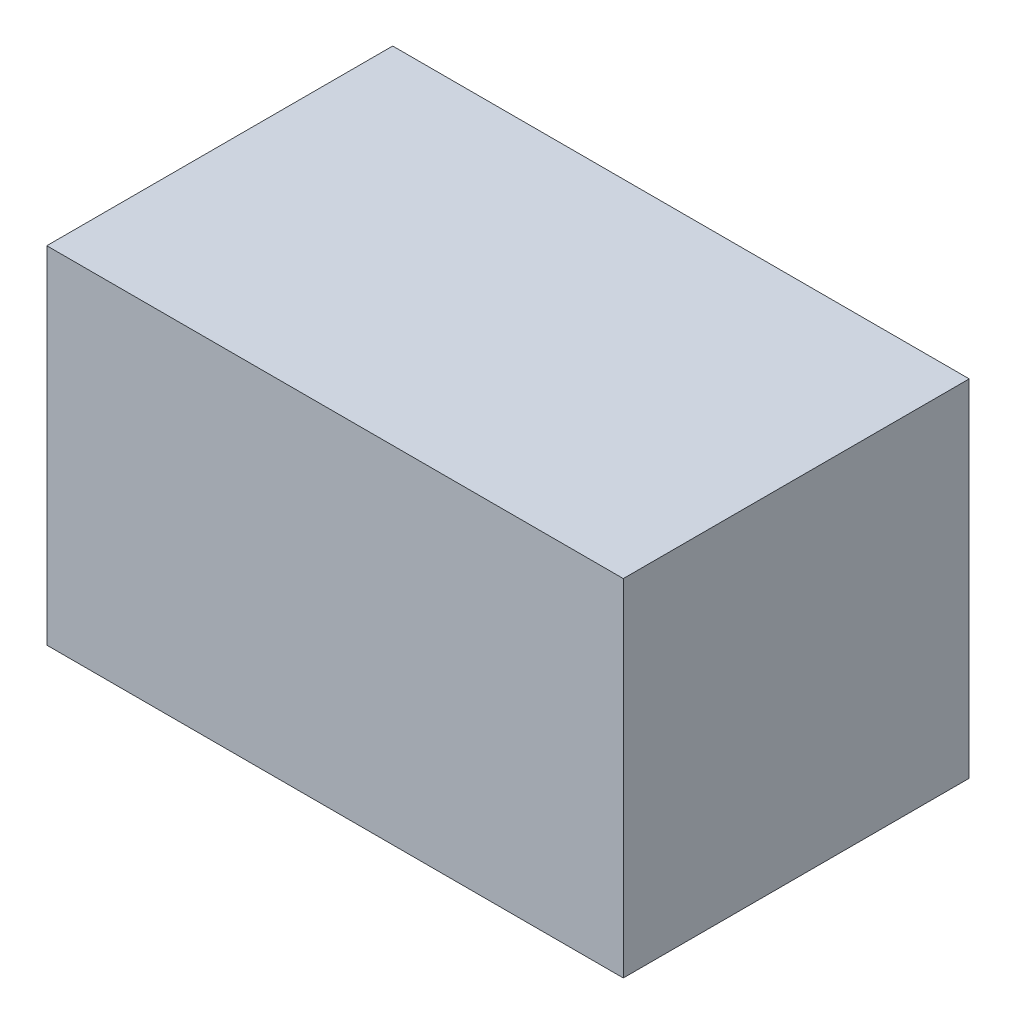
SolidWorks part; units mm, degrees
ref_plane "정면" through (0, 0, 0) normal (0, 0, 1) x (1, 0, 0)
ref_plane "윗면" through (0, 0, 0) normal (0, 1, 0) x (1, 0, 0)
ref_plane "우측면" through (0, 0, 0) normal (1, 0, 0) x (0, 0, -1)
sketch "스케치1" plane through (0, 0, 0) normal (0, 0, 1) x (1, 0, 0)
  line L1 (-25, 15) -> (25, 15)
  line L2 (-25, 15) -> (-25, -15)
  line L3 (-25, -15) -> (25, -15)
  line L4 (25, 15) -> (25, -15)
  line L5 (-25, 15) -> (25, -15) construction
  line L6 (-25, -15) -> (25, 15) construction
  point P0 (0, 0)
  dimension "D1" = 30
  dimension "D2" = 50
extrude "보스-돌출1" add sketch "스케치1" along normal blind 30
